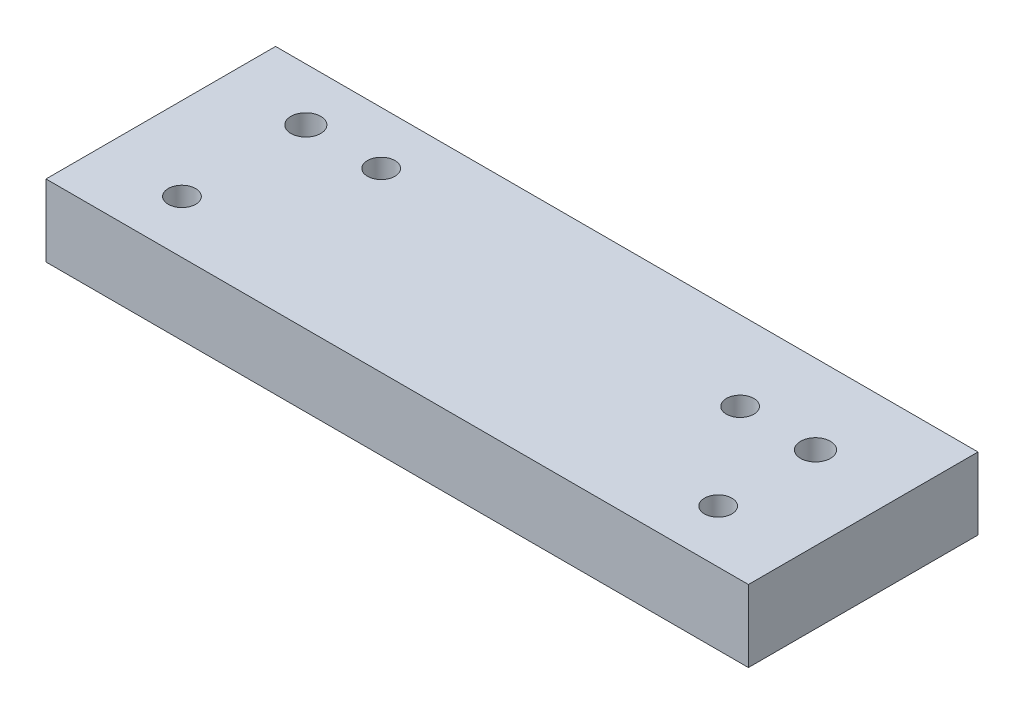
SolidWorks part; units mm, degrees
ref_plane "Front Plane" through (0, 0, 0) normal (0, 0, 1) x (1, 0, 0)
ref_plane "Top Plane" through (0, 0, 0) normal (0, 1, 0) x (1, 0, 0)
ref_plane "Right Plane" through (0, 0, 0) normal (1, 0, 0) x (0, 0, -1)
sketch "Sketch1" plane through (0, 0, 0) normal (0, 1, 0) x (1, 0, 0)
  line L1 (-102.5, 33.5) -> (102.5, 33.5)
  line L2 (-102.5, 33.5) -> (-102.5, -33.5)
  line L3 (-102.5, -33.5) -> (102.5, -33.5)
  line L4 (102.5, 33.5) -> (102.5, -33.5)
  line L5 (-102.5, 33.5) -> (102.5, -33.5) construction
  line L6 (-102.5, -33.5) -> (102.5, 33.5) construction
  point P0 (0, 0)
  dimension "D1" = 205
  dimension "D2" = 67
extrude "Boss-Extrude1" add sketch "Sketch1" along normal blind 21
sketch "Sketch2" plane through (0, 0, -21) normal (0, -1, 0) x (1, 0, 0)
  line L0 (-102.5, -12.5) -> (-102.5, 54.5) construction
  line L1 (-82.6, 2.925) -> (-102.5, 2.925) construction
  line L2 (102.5, 54.5) -> (102.5, -12.5) construction
  line L3 (82.6, 10.675) -> (102.5, 10.675) construction
  line L4 (-102.5, 54.5) -> (102.5, 54.5) construction
  line L5 (78.25, 10.675) -> (78.25, 39.075) construction
  line L6 (102.5, -12.5) -> (-102.5, -12.5) construction
  line L7 (-78.25, 2.925) -> (-78.25, 39.075) construction
  line L8 (-102.5, 21) -> (102.5, 21) construction
  line L11 (-64.6, 54.5) -> (-64.6, -12.5) construction
  line L14 (-48.6, 54.5) -> (-48.6, -12.5) construction
  line L15 (102.5, 0.175) -> (-102.5, 0.175) construction
  line L16 (-56.25, 2.925) -> (-78.25, 2.925) construction
  line L17 (64.6, 54.5) -> (64.6, -12.5) construction
  line L18 (56.25, 10.675) -> (78.25, 10.675) construction
  circle A0 centre (-78.25, 2.925) radius 4.35
  circle A1 centre (78.25, 10.675) radius 4.35
  circle A6 centre (-56.25, 2.925) radius 4
  circle A7 centre (56.25, 10.675) radius 4
  circle A8 centre (78.25, 39.075) radius 4
  circle A9 centre (-78.25, 39.075) radius 4
  point P10 (-78.25, 21)
  point P48 (-78.25, 21)
  dimension "D1" = 8.7
  dimension "D2" = 156.5
  dimension "D3" = 7.75
  dimension "D4" = 36.15
  dimension "D5" = 28.4
  dimension "D6" = 13.65
  dimension "D7" = 29.65
  dimension "D8" = 8
  dimension "D9" = 22
  dimension "D12" = 22
  dimension "D10" = 13.65
  dimension "D11" = 10.5
extrude "Cut-Extrude1" cut sketch "Sketch2" against normal up to surface (21 mm away) up to face at (0, 21, 0)
